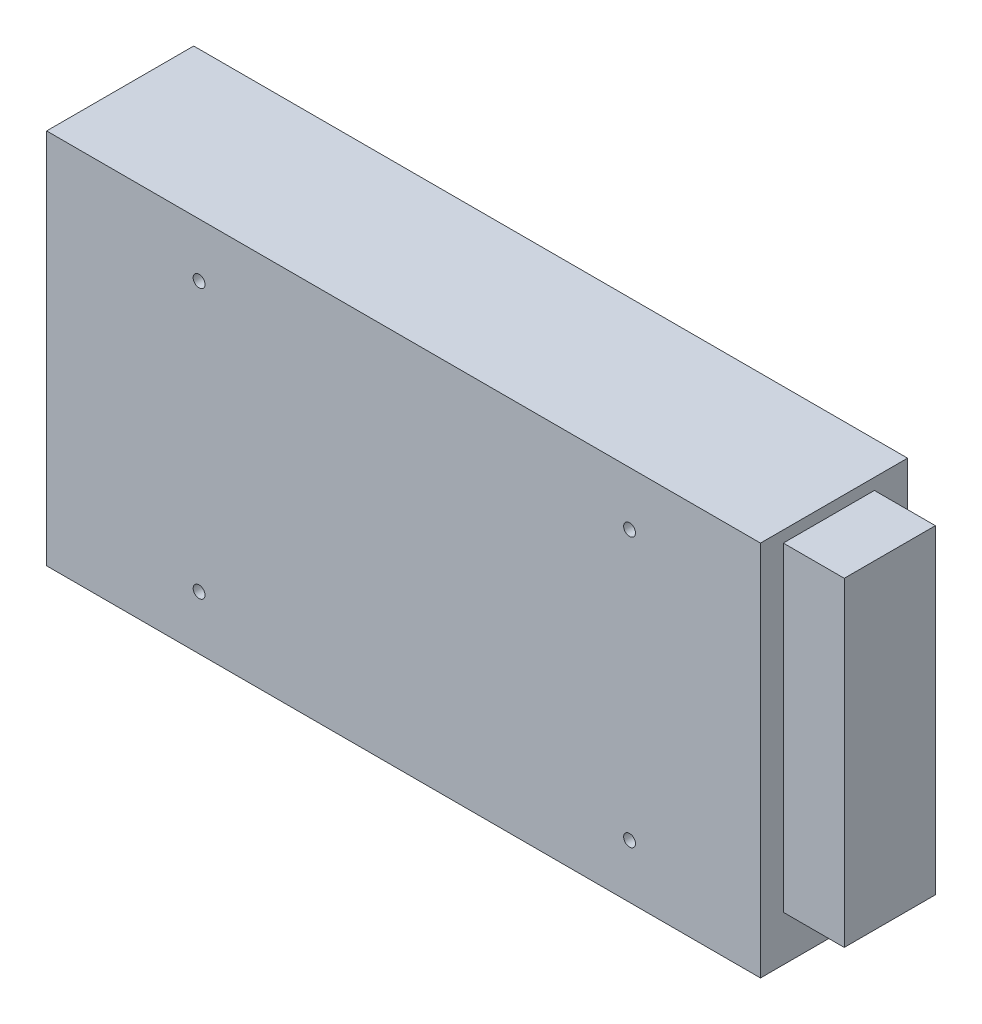
SolidWorks part; units mm, degrees
material "Plain Carbon Steel"
ref_plane "Front Plane" through (0, 0, 0) normal (0, 0, 1) x (1, 0, 0)
ref_plane "Top Plane" through (0, 0, 0) normal (0, 1, 0) x (1, 0, 0)
ref_plane "Right Plane" through (0, 0, 0) normal (1, 0, 0) x (0, 0, -1)
sketch "Sketch1" plane through (0, 0, 0) normal (0, 1, 0) x (1, 0, 0)
  line L1 (-99.5, 20.5) -> (99.5, 20.5)
  line L2 (-99.5, 20.5) -> (-99.5, -20.5)
  line L3 (-99.5, -20.5) -> (99.5, -20.5)
  line L4 (99.5, 20.5) -> (99.5, -20.5)
  line L5 (-99.5, 20.5) -> (99.5, -20.5) construction
  line L6 (-99.5, -20.5) -> (99.5, 20.5) construction
  point P0 (0, 0)
  dimension "D1" = 41
  dimension "D2" = 199
extrude "Boss-Extrude1" add sketch "Sketch1" along normal mid plane 105
sketch "Sketch2" plane through (0, 0, 20.5) normal (0, 0, 1) x (1, 0, 0)
  line L1 (194.341, 14.187) -> (105.441, 14.187)
  line L2 (194.341, 14.187) -> (194.341, -36.613)
  line L3 (194.341, -36.613) -> (105.441, -36.613)
  line L4 (105.441, 14.187) -> (105.441, -36.613)
  dimension "D1" = 50.8
  dimension "D2" = 88.9
extrude "Boss-Extrude2" [suppressed] add sketch "Sketch2" against normal blind 6.35 separate body
pattern_linear "LPattern1" [suppressed] count 2 spacing 19.05
shell "Shell1" [suppressed] thickness 3.175
fillet "Fillet1" [suppressed] radius 1.27
sketch "Sketch3" plane through (0, -52.5, 0) normal (0, -1, 0) x (1, 0, 0)
  line L0 (-74.1, 12.7) -> (-74.1, -12.7) construction
  line L1 (-72.5125, 12.7) -> (-72.5125, -12.7)
  line L2 (-75.6875, 12.7) -> (-75.6875, -12.7)
  line L3 (-99.5, -20.5) -> (-99.5, 20.5) construction
  arc A0 (-72.5125, 12.7) -> (-75.6875, 12.7) centre (-74.1, 12.7) ccw
  arc A1 (-75.6875, -12.7) -> (-72.5125, -12.7) centre (-74.1, -12.7) ccw
  point P2 (-74.1, 0)
  dimension "D2" = 1.5875
  dimension "D1" = 25.4
  dimension "D3" = 25.4
extrude "Cut-Extrude1" [suppressed] cut sketch "Sketch3" against normal through all
pattern_linear "LPattern2" [suppressed] count 21 spacing 10.16
sketch "Sketch4" [suppressed] plane through (0, 0, -26) normal (0, 0, -1) x (-1, 0, 0)
  line L0 (125, 51.43) -> (-125, 51.43) construction
  line L1 (-125, 51.43) -> (-125, -51.43) construction
  circle A0 centre (-118.65, 45.08) radius 2.3813
  dimension "D3" = 4.7625
  dimension "D1" = 6.35
  dimension "D2" = 6.35
extrude "Cut-Extrude2" [suppressed] cut sketch "Sketch4" against normal up to surface (3.175 mm away)
pattern_linear "LPattern3" [suppressed] count 24 spacing 10.16 count 10 spacing 10.16
ref_plane "Plane1" [suppressed] through (0, 0, 27) normal (0, 0, 1) x (1, 0, 0)
sketch "Sketch5" [suppressed] plane through (0, 0, 27) normal (0, 0, 1) x (1, 0, 0)
  line L0 (-125, 49.525) -> (125, 49.525) construction
  line L1 (-111, 46.35) -> (111, 46.35)
  line L2 (-111, 46.35) -> (-111, -46.35)
  line L3 (-111, -46.35) -> (111, -46.35)
  line L4 (111, 46.35) -> (111, -46.35)
  line L5 (-111, 46.35) -> (111, -46.35) construction
  line L6 (-111, -46.35) -> (111, 46.35) construction
  point P0 (0, 0)
  dimension "D1" = 3.175
  dimension "D2" = 222
extrude "Boss-Extrude3" [suppressed] add sketch "Sketch5" against normal blind 3.175 separate body
hole_wizard "Ø4.0mm Dowel Hole1" [suppressed] positions "Sketch7" profile "Sketch6" hole size "Ø4.0" standard "ANSI Metric"
sketch "Sketch7" [suppressed] plane through (0, 0, 23.825) normal (0, 0, -1) x (-1, 0, 0)
  line L8 (-106, 42.5) -> (106, 42.5) construction
  line L9 (-106, 42.5) -> (-106, -42.5) construction
  line L10 (-106, -42.5) -> (106, -42.5) construction
  line L11 (106, 42.5) -> (106, -42.5) construction
  line L12 (0, 42.5) -> (0, 0) construction
  line L14 (0, 0) -> (106, 0) construction
  point P281 (-106, 42.5)
  point P282 (106, -42.5)
  point P591 (-106, -42.5)
  point P592 (106, 42.5)
  dimension "D1" = 212
  dimension "D2" = 85
sketch "Sketch6" plane through (106, 42.5, 23.825) normal (1, 0, 0) x (0, 1, 0)
  line L0 (0, 0) -> (0, 10.8537)
  line L1 (0, 10.8537) -> (2, 9.652)
  line L2 (2, 9.652) -> (2, 0)
  line L5 (2, 0) -> (0, 0)
  line L10 (0, 10.8537) -> (-2, 9.652) construction
  line L11 (0, -6.35) -> (0, 107.95) construction
  dimension "Hole Dia." = 4
  dimension "Hole Depth" = 9.652
  dimension "Drill Angle" = 118
sketch "Sketch8" [suppressed] plane through (0, 0, 23.825) normal (0, 0, -1) x (-1, 0, 0)
  line L0 (-111, 46.35) -> (111, 46.35) construction
  line L1 (-81.2816, 46.35) -> (96.5184, 46.35)
  line L2 (-81.2816, 46.35) -> (-81.2816, 33.65)
  line L3 (-81.2816, 33.65) -> (96.5184, 33.65)
  line L4 (96.5184, 46.35) -> (96.5184, 33.65)
  line L5 (111, -46.35) -> (-111, -46.35) construction
  line L6 (-93.8366, -46.35) -> (7.7634, -46.35)
  line L7 (-93.8366, -46.35) -> (-93.8366, -33.65)
  line L8 (-93.8366, -33.65) -> (7.7634, -33.65)
  line L9 (7.7634, -46.35) -> (7.7634, -33.65)
  line L11 (46.6512, -46.35) -> (72.0512, -46.35)
  line L12 (46.6512, -46.35) -> (46.6512, -33.65)
  line L13 (46.6512, -33.65) -> (72.0512, -33.65)
  line L14 (72.0512, -46.35) -> (72.0512, -33.65)
  dimension "D1" = 177.8
  dimension "D2" = 12.7
  dimension "D3" = 12.7
  dimension "D4" = 101.6
  dimension "D5" = 12.7
  dimension "D6" = 25.4
extrude "Boss-Extrude4" [suppressed] add sketch "Sketch8" along normal blind 25.4 separate body
sketch "Sketch9" [suppressed] plane through (0, 0, 23.825) normal (0, 0, -1) x (-1, 0, 0)
  line L0 (-111, -46.35) -> (-111, 46.35) construction
  line L1 (-111, 25.5565) -> (-101.475, 25.5565)
  line L2 (-111, 25.5565) -> (-111, 0.1565)
  line L3 (-111, 0.1565) -> (-101.475, 0.1565)
  line L4 (-101.475, 25.5565) -> (-101.475, 0.1565)
  line L5 (111, 46.35) -> (111, -46.35) construction
  line L6 (111, -29.9065) -> (101.475, -29.9065)
  line L7 (111, -29.9065) -> (111, -4.5065)
  line L8 (111, -4.5065) -> (101.475, -4.5065)
  line L9 (101.475, -29.9065) -> (101.475, -4.5065)
  dimension "D1" = 9.525
  dimension "D2" = 25.4
  dimension "D3" = 9.525
  dimension "D4" = 25.4
extrude "Boss-Extrude5" [suppressed] add sketch "Sketch9" along normal blind 12.7 separate body
sketch "Sketch10" plane through (99.5, 0, 0) normal (1, 0, 0) x (0, 0, -1)
  line L0 (-20.5, 52.5) -> (20.5, 52.5) construction
  line L1 (-14.15, 49.325) -> (11.25, 49.325)
  line L2 (-14.15, 49.325) -> (-14.15, -39.8)
  line L3 (-14.15, -39.8) -> (11.25, -39.8)
  line L4 (11.25, 49.325) -> (11.25, -39.8)
  line L5 (-14.15, 49.325) -> (11.25, -39.8) construction
  line L6 (-14.15, -39.8) -> (11.25, 49.325) construction
  line L7 (-20.5, -52.5) -> (20.5, -52.5) construction
  line L8 (-20.5, 52.5) -> (-20.5, -52.5) construction
  point P0 (-1.45, 4.7625)
  dimension "D1" = 25.4
  dimension "D2" = 3.175
  dimension "D3" = 12.7
  dimension "D4" = 6.35
extrude "Boss-Extrude6" add sketch "Sketch10" along normal blind 17
hole_wizard "M4x0.7 Tapped Hole1" positions "Sketch13" profile "Sketch11" tap size "M4x0.7" standard "ANSI Metric"
sketch "Sketch13" plane through (0, 0, 20.5) normal (0, 0, 1) x (1, 0, 0)
  line L1 (-57, 37.5) -> (63, 37.5) construction
  line L2 (-57, 37.5) -> (-57, -37.5) construction
  line L3 (-57, -37.5) -> (63, -37.5) construction
  line L4 (63, 37.5) -> (63, -37.5) construction
  line L5 (-99.5, -52.5) -> (99.5, -52.5) construction
  line L6 (-99.5, 52.5) -> (-99.5, -52.5) construction
  point P1 (-57, 37.5)
  point P2 (63, -37.5)
  point P209 (-57, -37.5)
  point P210 (63, 37.5)
  dimension "D1" = 120
  dimension "D2" = 75
  dimension "D3" = 15
  dimension "D4" = 42.5
sketch "Sketch11" plane through (-57, 37.5, 20.5) normal (1, 0, 0) x (0, -1, 0)
  line L0 (0, 0) -> (0, 10.8974)
  line L1 (0, 10.8974) -> (1.65, 9.906)
  line L2 (1.65, 9.906) -> (1.65, 0)
  line L5 (1.65, 0) -> (0, 0)
  line L10 (0, 10.8974) -> (-1.65, 9.906) construction
  line L11 (0, -6.35) -> (0, 107.95) construction
  dimension "Tap Drill Dia." = 3.3
  dimension "Tap Drill Depth" = 9.906
  dimension "Drill Angle" = 118
